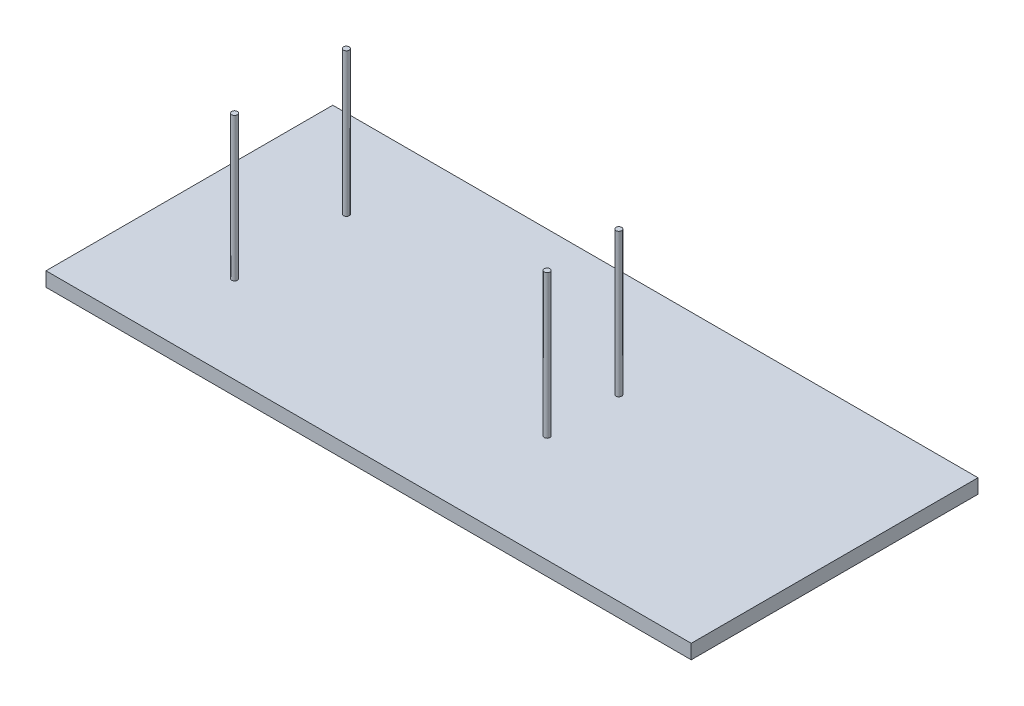
SolidWorks part; units mm, degrees
material "AISI 1010 钢，热轧条材"
ref_plane "前视基准面" through (0, 0, 0) normal (0, 0, 1) x (1, 0, 0)
ref_plane "上视基准面" through (0, 0, 0) normal (0, 1, 0) x (1, 0, 0)
ref_plane "右视基准面" through (0, 0, 0) normal (1, 0, 0) x (0, 0, -1)
sketch "草图1" plane through (0, 0, 0) normal (0, 1, 0) x (1, 0, 0)
  line L1 (-300, -100) -> (300, -100)
  line L2 (-300, -100) -> (-300, 100)
  line L3 (-300, 100) -> (300, 100)
  line L4 (300, -100) -> (300, 100)
  line L5 (-300, -100) -> (300, 100) construction
  line L6 (-300, 100) -> (300, -100) construction
  point P0 (0, 0)
  dimension "D1" = 200
  dimension "D2" = 600
extrude "凸台-拉伸1" add sketch "草图1" against normal blind 10
sketch "草图2" plane through (0, 0, 0) normal (0, 1, 0) x (1, 0, 0)
  line L0 (-129.5, 100) -> (-129.5, -100) construction
  line L1 (300, 100) -> (-300, 100) construction
  line L2 (-300, -100) -> (300, -100) construction
  line L3 (-300, 100) -> (-300, -100) construction
  line L4 (-129.5, 0) -> (73.6363, 0) construction
  line L5 (74.5, 100) -> (74.5, -100) construction
  line L6 (300, -100) -> (300, 100) construction
  circle A0 centre (-129.5, 39) radius 2
  circle A1 centre (-129.5, -39) radius 2
  circle A2 centre (74.5, 25) radius 2
  circle A3 centre (74.5, -25) radius 2
  dimension "D2" = 4
  dimension "D5" = 4
  dimension "D1" = 170.5
  dimension "D3" = 78
  dimension "D4" = 225.5
  dimension "D6" = 50
extrude "凸台-拉伸2" add sketch "草图2" along normal blind 100
sketch "草图3" plane through (0, 0, 0) normal (0, 1, 0) x (1, 0, 0)
  line L0 (-300, -100) -> (300, -100) construction
  line L1 (-300, 100) -> (-200, 100)
  line L2 (-300, 100) -> (-300, -100)
  line L3 (-300, -100) -> (-200, -100)
  line L4 (-200, 100) -> (-200, -100)
  line L6 (300, 100) -> (250, 100)
  line L7 (300, 100) -> (300, -100)
  line L8 (300, -100) -> (250, -100)
  line L9 (250, 100) -> (250, -100)
  dimension "D1" = 100
  dimension "D2" = 50
extrude "切除-拉伸1" cut sketch "草图3" against normal blind 10
